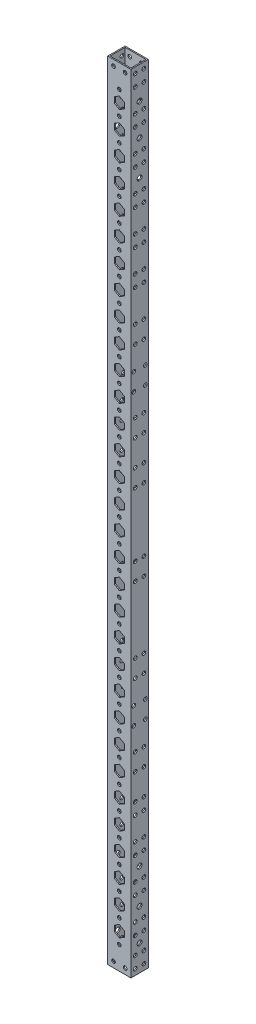
SolidWorks part; units mm, degrees
ref_plane "前视基准面" through (0, 0, 0) normal (0, 0, 1) x (1, 0, 0)
ref_plane "上视基准面" through (0, 0, 0) normal (0, 1, 0) x (1, 0, 0)
ref_plane "右视基准面" through (0, 0, 0) normal (1, 0, 0) x (0, 0, -1)
other "Configuration Table"
sketch "草图1" plane through (0, 0, 0) normal (0, 1, 0) x (1, 0, 0)
  line L1 (-10, -7.5) -> (10, -7.5)
  line L2 (-10, -7.5) -> (-10, 7.5)
  line L3 (-10, 7.5) -> (10, 7.5)
  line L4 (10, -7.5) -> (10, 7.5)
  line L5 (-10, -7.5) -> (10, 7.5) construction
  line L6 (-10, 7.5) -> (10, -7.5) construction
  point P0 (0, 0)
  dimension "D1" = 15
  dimension "D2" = 20
extrude "拉伸-薄壁1" add sketch "草图1" along normal blind 680 thin thin type one direction reverse wall 1
sketch "草图2" plane through (0, 0, -7.5) normal (0, 0, -1) x (-1, 0, 0)
  line L0 (0, 680) -> (0, 670) construction
  line L1 (-10, 680) -> (10, 680) construction
  line L2 (0, 670) -> (-10, 670) construction
  line L3 (-10, 680) -> (-10, 0) construction
  line L4 (10, 340) -> (-10, 340) construction
  line L5 (10, 680) -> (10, 0) construction
  line L6 (0, 10) -> (-10, 10) construction
  line L7 (0, 0) -> (0, 10) construction
  line L8 (0, 20) -> (0, 40) construction
  line L9 (-4.3301, 32.5008) -> (-4.3301, 27.5008)
  line L10 (-4.3301, 27.5008) -> (0, 25.0008)
  line L11 (0, 25.0008) -> (4.3301, 27.5008)
  line L12 (4.3301, 27.5008) -> (4.3301, 32.5008)
  line L13 (4.3301, 32.5008) -> (0, 35.0008)
  line L14 (0, 35.0008) -> (-4.3301, 32.5008)
  line L15 (0, 55.0008) -> (-4.3301, 52.5008)
  line L16 (4.3301, 52.5008) -> (0, 55.0008)
  line L17 (4.3301, 47.5008) -> (4.3301, 52.5008)
  line L18 (-4.3301, 52.5008) -> (-4.3301, 47.5008)
  line L19 (-4.3301, 47.5008) -> (0, 45.0008)
  line L20 (0, 45.0008) -> (4.3301, 47.5008)
  line L21 (0, 75.0008) -> (-4.3301, 72.5008)
  line L22 (4.3301, 72.5008) -> (0, 75.0008)
  line L23 (4.3301, 67.5008) -> (4.3301, 72.5008)
  line L24 (-4.3301, 72.5008) -> (-4.3301, 67.5008)
  line L25 (-4.3301, 67.5008) -> (0, 65.0008)
  line L26 (0, 65.0008) -> (4.3301, 67.5008)
  line L27 (0, 95.0008) -> (-4.3301, 92.5008)
  line L28 (4.3301, 92.5008) -> (0, 95.0008)
  line L29 (4.3301, 87.5008) -> (4.3301, 92.5008)
  line L30 (-4.3301, 92.5008) -> (-4.3301, 87.5008)
  line L31 (-4.3301, 87.5008) -> (0, 85.0008)
  line L32 (0, 85.0008) -> (4.3301, 87.5008)
  line L33 (0, 115.0008) -> (-4.3301, 112.5008)
  line L34 (4.3301, 112.5008) -> (0, 115.0008)
  line L35 (4.3301, 107.5008) -> (4.3301, 112.5008)
  line L36 (-4.3301, 112.5008) -> (-4.3301, 107.5008)
  line L37 (-4.3301, 107.5008) -> (0, 105.0008)
  line L38 (0, 105.0008) -> (4.3301, 107.5008)
  line L39 (0, 135.0008) -> (-4.3301, 132.5008)
  line L40 (4.3301, 132.5008) -> (0, 135.0008)
  line L41 (4.3301, 127.5008) -> (4.3301, 132.5008)
  line L42 (-4.3301, 132.5008) -> (-4.3301, 127.5008)
  line L43 (-4.3301, 127.5008) -> (0, 125.0008)
  line L44 (0, 125.0008) -> (4.3301, 127.5008)
  line L45 (0, 155.0008) -> (-4.3301, 152.5008)
  line L46 (4.3301, 152.5008) -> (0, 155.0008)
  line L47 (4.3301, 147.5008) -> (4.3301, 152.5008)
  line L48 (-4.3301, 152.5008) -> (-4.3301, 147.5008)
  line L49 (-4.3301, 147.5008) -> (0, 145.0008)
  line L50 (0, 145.0008) -> (4.3301, 147.5008)
  line L51 (0, 175.0008) -> (-4.3301, 172.5008)
  line L52 (4.3301, 172.5008) -> (0, 175.0008)
  line L53 (4.3301, 167.5008) -> (4.3301, 172.5008)
  line L54 (-4.3301, 172.5008) -> (-4.3301, 167.5008)
  line L55 (-4.3301, 167.5008) -> (0, 165.0008)
  line L56 (0, 165.0008) -> (4.3301, 167.5008)
  line L57 (0, 195.0008) -> (-4.3301, 192.5008)
  line L58 (4.3301, 192.5008) -> (0, 195.0008)
  line L59 (4.3301, 187.5008) -> (4.3301, 192.5008)
  line L60 (-4.3301, 192.5008) -> (-4.3301, 187.5008)
  line L61 (-4.3301, 187.5008) -> (0, 185.0008)
  line L62 (0, 185.0008) -> (4.3301, 187.5008)
  line L63 (0, 215.0008) -> (-4.3301, 212.5008)
  line L64 (4.3301, 212.5008) -> (0, 215.0008)
  line L65 (4.3301, 207.5008) -> (4.3301, 212.5008)
  line L66 (-4.3301, 212.5008) -> (-4.3301, 207.5008)
  line L67 (-4.3301, 207.5008) -> (0, 205.0008)
  line L68 (0, 205.0008) -> (4.3301, 207.5008)
  line L69 (0, 235.0008) -> (-4.3301, 232.5008)
  line L70 (4.3301, 232.5008) -> (0, 235.0008)
  line L71 (4.3301, 227.5008) -> (4.3301, 232.5008)
  line L72 (-4.3301, 232.5008) -> (-4.3301, 227.5008)
  line L73 (-4.3301, 227.5008) -> (0, 225.0008)
  line L74 (0, 225.0008) -> (4.3301, 227.5008)
  line L75 (0, 255.0008) -> (-4.3301, 252.5008)
  line L76 (4.3301, 252.5008) -> (0, 255.0008)
  line L77 (4.3301, 247.5008) -> (4.3301, 252.5008)
  line L78 (-4.3301, 252.5008) -> (-4.3301, 247.5008)
  line L79 (-4.3301, 247.5008) -> (0, 245.0008)
  line L80 (0, 245.0008) -> (4.3301, 247.5008)
  line L81 (0, 275.0008) -> (-4.3301, 272.5008)
  line L82 (4.3301, 272.5008) -> (0, 275.0008)
  line L83 (4.3301, 267.5008) -> (4.3301, 272.5008)
  line L84 (-4.3301, 272.5008) -> (-4.3301, 267.5008)
  line L85 (-4.3301, 267.5008) -> (0, 265.0008)
  line L86 (0, 265.0008) -> (4.3301, 267.5008)
  line L87 (0, 295.0008) -> (-4.3301, 292.5008)
  line L88 (4.3301, 292.5008) -> (0, 295.0008)
  line L89 (4.3301, 287.5008) -> (4.3301, 292.5008)
  line L90 (-4.3301, 292.5008) -> (-4.3301, 287.5008)
  line L91 (-4.3301, 287.5008) -> (0, 285.0008)
  line L92 (0, 285.0008) -> (4.3301, 287.5008)
  line L93 (0, 315.0008) -> (-4.3301, 312.5008)
  line L94 (4.3301, 312.5008) -> (0, 315.0008)
  line L95 (4.3301, 307.5008) -> (4.3301, 312.5008)
  line L96 (-4.3301, 312.5008) -> (-4.3301, 307.5008)
  line L97 (-4.3301, 307.5008) -> (0, 305.0008)
  line L98 (0, 305.0008) -> (4.3301, 307.5008)
  line L99 (0, 335.0008) -> (-4.3301, 332.5008)
  line L100 (4.3301, 332.5008) -> (0, 335.0008)
  line L101 (4.3301, 327.5008) -> (4.3301, 332.5008)
  line L102 (-4.3301, 332.5008) -> (-4.3301, 327.5008)
  line L103 (-4.3301, 327.5008) -> (0, 325.0008)
  line L104 (0, 325.0008) -> (4.3301, 327.5008)
  line L105 (0, 355.0008) -> (-4.3301, 352.5008)
  line L106 (4.3301, 352.5008) -> (0, 355.0008)
  line L107 (4.3301, 347.5008) -> (4.3301, 352.5008)
  line L108 (-4.3301, 352.5008) -> (-4.3301, 347.5008)
  line L109 (-4.3301, 347.5008) -> (0, 345.0008)
  line L110 (0, 345.0008) -> (4.3301, 347.5008)
  line L111 (0, 375.0008) -> (-4.3301, 372.5008)
  line L112 (4.3301, 372.5008) -> (0, 375.0008)
  line L113 (4.3301, 367.5008) -> (4.3301, 372.5008)
  line L114 (-4.3301, 372.5008) -> (-4.3301, 367.5008)
  line L115 (-4.3301, 367.5008) -> (0, 365.0008)
  line L116 (0, 365.0008) -> (4.3301, 367.5008)
  line L117 (0, 395.0008) -> (-4.3301, 392.5008)
  line L118 (4.3301, 392.5008) -> (0, 395.0008)
  line L119 (4.3301, 387.5008) -> (4.3301, 392.5008)
  line L120 (-4.3301, 392.5008) -> (-4.3301, 387.5008)
  line L121 (-4.3301, 387.5008) -> (0, 385.0008)
  line L122 (0, 385.0008) -> (4.3301, 387.5008)
  line L123 (0, 415.0008) -> (-4.3301, 412.5008)
  line L124 (4.3301, 412.5008) -> (0, 415.0008)
  line L125 (4.3301, 407.5008) -> (4.3301, 412.5008)
  line L126 (-4.3301, 412.5008) -> (-4.3301, 407.5008)
  line L127 (-4.3301, 407.5008) -> (0, 405.0008)
  line L128 (0, 405.0008) -> (4.3301, 407.5008)
  line L129 (0, 435.0008) -> (-4.3301, 432.5008)
  line L130 (4.3301, 432.5008) -> (0, 435.0008)
  line L131 (4.3301, 427.5008) -> (4.3301, 432.5008)
  line L132 (-4.3301, 432.5008) -> (-4.3301, 427.5008)
  line L133 (-4.3301, 427.5008) -> (0, 425.0008)
  line L134 (0, 425.0008) -> (4.3301, 427.5008)
  line L135 (0, 455.0008) -> (-4.3301, 452.5008)
  line L136 (4.3301, 452.5008) -> (0, 455.0008)
  line L137 (4.3301, 447.5008) -> (4.3301, 452.5008)
  line L138 (-4.3301, 452.5008) -> (-4.3301, 447.5008)
  line L139 (-4.3301, 447.5008) -> (0, 445.0008)
  line L140 (0, 445.0008) -> (4.3301, 447.5008)
  line L141 (0, 475.0008) -> (-4.3301, 472.5008)
  line L142 (4.3301, 472.5008) -> (0, 475.0008)
  line L143 (4.3301, 467.5008) -> (4.3301, 472.5008)
  line L144 (-4.3301, 472.5008) -> (-4.3301, 467.5008)
  line L145 (-4.3301, 467.5008) -> (0, 465.0008)
  line L146 (0, 465.0008) -> (4.3301, 467.5008)
  line L147 (0, 495.0008) -> (-4.3301, 492.5008)
  line L148 (4.3301, 492.5008) -> (0, 495.0008)
  line L149 (4.3301, 487.5008) -> (4.3301, 492.5008)
  line L150 (-4.3301, 492.5008) -> (-4.3301, 487.5008)
  line L151 (-4.3301, 487.5008) -> (0, 485.0008)
  line L152 (0, 485.0008) -> (4.3301, 487.5008)
  line L153 (0, 515.0008) -> (-4.3301, 512.5008)
  line L154 (4.3301, 512.5008) -> (0, 515.0008)
  line L155 (4.3301, 507.5008) -> (4.3301, 512.5008)
  line L156 (-4.3301, 512.5008) -> (-4.3301, 507.5008)
  line L157 (-4.3301, 507.5008) -> (0, 505.0008)
  line L158 (0, 505.0008) -> (4.3301, 507.5008)
  line L159 (0, 535.0008) -> (-4.3301, 532.5008)
  line L160 (4.3301, 532.5008) -> (0, 535.0008)
  line L161 (4.3301, 527.5008) -> (4.3301, 532.5008)
  line L162 (-4.3301, 532.5008) -> (-4.3301, 527.5008)
  line L163 (-4.3301, 527.5008) -> (0, 525.0008)
  line L164 (0, 525.0008) -> (4.3301, 527.5008)
  line L165 (0, 555.0008) -> (-4.3301, 552.5008)
  line L166 (4.3301, 552.5008) -> (0, 555.0008)
  line L167 (4.3301, 547.5008) -> (4.3301, 552.5008)
  line L168 (-4.3301, 552.5008) -> (-4.3301, 547.5008)
  line L169 (-4.3301, 547.5008) -> (0, 545.0008)
  line L170 (0, 545.0008) -> (4.3301, 547.5008)
  line L171 (0, 575.0008) -> (-4.3301, 572.5008)
  line L172 (4.3301, 572.5008) -> (0, 575.0008)
  line L173 (4.3301, 567.5008) -> (4.3301, 572.5008)
  line L174 (-4.3301, 572.5008) -> (-4.3301, 567.5008)
  line L175 (-4.3301, 567.5008) -> (0, 565.0008)
  line L176 (0, 565.0008) -> (4.3301, 567.5008)
  line L177 (0, 595.0008) -> (-4.3301, 592.5008)
  line L178 (4.3301, 592.5008) -> (0, 595.0008)
  line L179 (4.3301, 587.5008) -> (4.3301, 592.5008)
  line L180 (-4.3301, 592.5008) -> (-4.3301, 587.5008)
  line L181 (-4.3301, 587.5008) -> (0, 585.0008)
  line L182 (0, 585.0008) -> (4.3301, 587.5008)
  line L183 (0, 615.0008) -> (-4.3301, 612.5008)
  line L184 (4.3301, 612.5008) -> (0, 615.0008)
  line L185 (4.3301, 607.5008) -> (4.3301, 612.5008)
  line L186 (-4.3301, 612.5008) -> (-4.3301, 607.5008)
  line L187 (-4.3301, 607.5008) -> (0, 605.0008)
  line L188 (0, 605.0008) -> (4.3301, 607.5008)
  line L189 (0, 635.0008) -> (-4.3301, 632.5008)
  line L190 (4.3301, 632.5008) -> (0, 635.0008)
  line L191 (4.3301, 627.5008) -> (4.3301, 632.5008)
  line L192 (-4.3301, 632.5008) -> (-4.3301, 627.5008)
  line L193 (-4.3301, 627.5008) -> (0, 625.0008)
  line L194 (0, 625.0008) -> (4.3301, 627.5008)
  line L195 (0, 655.0008) -> (-4.3301, 652.5008)
  line L196 (4.3301, 652.5008) -> (0, 655.0008)
  line L197 (4.3301, 647.5008) -> (4.3301, 652.5008)
  line L198 (-4.3301, 652.5008) -> (-4.3301, 647.5008)
  line L199 (-4.3301, 647.5008) -> (0, 645.0008)
  line L200 (0, 645.0008) -> (4.3301, 647.5008)
  circle A0 centre (-5, 675) radius 1.575
  circle A1 centre (5, 675) radius 1.575
  circle A2 centre (5, 5) radius 1.575
  circle A3 centre (-5, 5) radius 1.575
  circle A4 centre (0, 660) radius 1.575
  circle A5 centre (0, 640) radius 1.575
  circle A6 centre (0, 620) radius 1.575
  circle A7 centre (0, 600) radius 1.575
  circle A8 centre (0, 580) radius 1.575
  circle A9 centre (0, 560) radius 1.575
  circle A10 centre (0, 540) radius 1.575
  circle A11 centre (0, 520) radius 1.575
  circle A12 centre (0, 500) radius 1.575
  circle A13 centre (0, 480) radius 1.575
  circle A14 centre (0, 460) radius 1.575
  circle A15 centre (0, 440) radius 1.575
  circle A16 centre (0, 420) radius 1.575
  circle A17 centre (0, 400) radius 1.575
  circle A18 centre (0, 380) radius 1.575
  circle A19 centre (0, 360) radius 1.575
  circle A20 centre (0, 340) radius 1.575
  circle A21 centre (0, 320) radius 1.575
  circle A22 centre (0, 300) radius 1.575
  circle A23 centre (0, 280) radius 1.575
  circle A24 centre (0, 260) radius 1.575
  circle A25 centre (0, 240) radius 1.575
  circle A26 centre (0, 220) radius 1.575
  circle A27 centre (0, 200) radius 1.575
  circle A28 centre (0, 180) radius 1.575
  circle A29 centre (0, 160) radius 1.575
  circle A30 centre (0, 140) radius 1.575
  circle A31 centre (0, 120) radius 1.575
  circle A32 centre (0, 100) radius 1.575
  circle A33 centre (0, 80) radius 1.575
  circle A34 centre (0, 60) radius 1.575
  circle A35 centre (0, 40) radius 1.575
  circle A36 centre (0, 20) radius 1.575
  circle A37 centre (0, 30.0008) radius 4.3301 construction
  dimension "D2" = 3.15
  dimension "D5" = 3.15
  dimension "D1" = 10
  dimension "D3" = 5
  dimension "D4" = 5
  dimension "D6" = 10
  dimension "D8" = 20
  dimension "D9" = 5
  dimension "D10" = 9.9992
  dimension "D11" = 20
  dimension "D7" = 33
extrude "切除-拉伸1" cut sketch "草图2" against normal through all
sketch "草图3" plane through (-10, 0, 0) normal (-1, 0, 0) x (0, 0, 1)
  line L0 (-7.5, 445) -> (7.5, 445) construction
  line L1 (-7.5, 680) -> (-7.5, 0) construction
  line L2 (7.5, 680) -> (7.5, 0) construction
  line L3 (-7.5, 680) -> (7.5, 680) construction
  line L4 (0, 445) -> (0, 680) construction
  line L5 (-7.5, 195) -> (7.5, 195) construction
  line L6 (-7.5, 160) -> (7.5, 160) construction
  line L7 (-7.5, 480) -> (7.5, 480) construction
  line L8 (-7.5, 230) -> (7.5, 230) construction
  line L9 (-7.5, 10) -> (7.5, 10) construction
  line L10 (0, 10) -> (0, 0) construction
  line L11 (-7.5, 0) -> (7.5, 0) construction
  line L12 (0, 337.5) -> (7.5, 337.5) construction
  line L13 (0, 445) -> (0, 230) construction
  line L14 (-7.5, 372.5) -> (7.5, 372.5) construction
  line L15 (-7.5, 302.5) -> (7.5, 302.5) construction
  line L16 (-7.5, 670) -> (7.5, 670) construction
  line L17 (0, 10) -> (0, 22.5) construction
  line L18 (0, 22.5) -> (0, 50) construction
  line L19 (0, 50) -> (0, 80) construction
  circle A0 centre (-5, 452.5) radius 1.575
  circle A1 centre (5, 452.5) radius 1.575
  circle A2 centre (5, 437.5) radius 1.575
  circle A3 centre (-5, 437.5) radius 1.575
  circle A4 centre (-5, 202.5) radius 1.575
  circle A5 centre (5, 202.5) radius 1.575
  circle A6 centre (5, 187.5) radius 1.575
  circle A7 centre (-5, 187.5) radius 1.575
  circle A8 centre (-3.75, 487.5) radius 1.575
  circle A9 centre (-3.75, 472.5) radius 1.575
  circle A10 centre (3.75, 472.5) radius 1.575
  circle A11 centre (3.75, 487.5) radius 1.575
  circle A12 centre (3.75, 417.5) radius 1.575
  circle A13 centre (-3.75, 417.5) radius 1.575
  circle A14 centre (3.75, 402.5) radius 1.575
  circle A15 centre (-3.75, 402.5) radius 1.575
  circle A16 centre (-3.75, 167.5) radius 1.575
  circle A17 centre (3.75, 167.5) radius 1.575
  circle A18 centre (3.75, 152.5) radius 1.575
  circle A19 centre (-3.75, 152.5) radius 1.575
  circle A20 centre (-3.75, 237.5) radius 1.575
  circle A21 centre (3.75, 237.5) radius 1.575
  circle A22 centre (3.75, 222.5) radius 1.575
  circle A23 centre (-3.75, 222.5) radius 1.575
  circle A24 centre (3.75, 5) radius 1.6
  circle A25 centre (-3.75, 5) radius 1.6
  circle A26 centre (3.75, 15) radius 1.6
  circle A27 centre (-3.75, 15) radius 1.6
  circle A28 centre (3.75, 365) radius 1.6
  circle A29 centre (-3.75, 365) radius 1.6
  circle A30 centre (-3.75, 380) radius 1.6
  circle A31 centre (3.75, 380) radius 1.6
  circle A32 centre (3.75, 295) radius 1.6
  circle A33 centre (-3.75, 295) radius 1.6
  circle A34 centre (-3.75, 310) radius 1.6
  circle A35 centre (3.75, 310) radius 1.6
  circle A36 centre (-3.75, 675) radius 1.6
  circle A37 centre (3.75, 675) radius 1.6
  circle A38 centre (3.75, 665) radius 1.6
  circle A39 centre (-3.75, 665) radius 1.6
  circle A40 centre (-3.75, 645) radius 1.6
  circle A41 centre (3.75, 645) radius 1.6
  circle A42 centre (-3.75, 635) radius 1.6
  circle A43 centre (3.75, 635) radius 1.6
  circle A44 centre (-3.75, 615) radius 1.6
  circle A45 centre (3.75, 615) radius 1.6
  circle A46 centre (-3.75, 605) radius 1.6
  circle A47 centre (3.75, 605) radius 1.6
  circle A48 centre (-3.75, 585) radius 1.6
  circle A49 centre (3.75, 585) radius 1.6
  circle A50 centre (-3.75, 575) radius 1.6
  circle A51 centre (3.75, 575) radius 1.6
  circle A52 centre (-3.75, 555) radius 1.6
  circle A53 centre (3.75, 555) radius 1.6
  circle A54 centre (-3.75, 545) radius 1.6
  circle A55 centre (3.75, 545) radius 1.6
  circle A56 centre (-3.75, 525) radius 1.6
  circle A57 centre (3.75, 525) radius 1.6
  circle A58 centre (-3.75, 515) radius 1.6
  circle A59 centre (3.75, 515) radius 1.6
  circle A60 centre (3.75, 130) radius 1.6
  circle A61 centre (-3.75, 130) radius 1.6
  circle A62 centre (3.75, 120) radius 1.6
  circle A63 centre (-3.75, 120) radius 1.6
  circle A64 centre (3.75, 100) radius 1.6
  circle A65 centre (-3.75, 100) radius 1.6
  circle A66 centre (3.75, 90) radius 1.6
  circle A67 centre (-3.75, 90) radius 1.6
  circle A68 centre (3.75, 70) radius 1.6
  circle A69 centre (-3.75, 70) radius 1.6
  circle A70 centre (3.75, 60) radius 1.6
  circle A71 centre (-3.75, 60) radius 1.6
  circle A72 centre (3.75, 40) radius 1.6
  circle A73 centre (-3.75, 40) radius 1.6
  circle A74 centre (3.75, 30) radius 1.6
  circle A75 centre (-3.75, 30) radius 1.6
  circle A76 centre (0, 22.5) radius 2.1
  circle A77 centre (0, 50) radius 2.1
  circle A78 centre (0, 652.5) radius 2.1
  circle A79 centre (0, 625) radius 2.1
  circle A80 centre (0, 80) radius 2.1
  circle A81 centre (0, 595) radius 2.1
  dimension "D3" = 3.15
  dimension "D6" = 3.15
  dimension "D11" = 3.15
  dimension "D14" = 3.15
  dimension "D17" = 3.2
  dimension "D22" = 3.2
  dimension "D25" = 3.2
  dimension "D30" = 4.2
  dimension "D32" = 4.2
  dimension "D35" = 4.2
  dimension "D1" = 235
  dimension "D2" = 5
  dimension "D4" = 7.5
  dimension "D5" = 250
  dimension "D7" = 7.5
  dimension "D8" = 5
  dimension "D9" = 35
  dimension "D10" = 35
  dimension "D12" = 3.75
  dimension "D13" = 7.5
  dimension "D15" = 7.5
  dimension "D16" = 3.75
  dimension "D18" = 5
  dimension "D19" = 10
  dimension "D20" = 3.75
  dimension "D21" = 35
  dimension "D23" = 3.75
  dimension "D24" = 7.5
  dimension "D26" = 3.75
  dimension "D27" = 5
  dimension "D28" = 10
  dimension "D29" = 30
  dimension "D31" = 12.5
  dimension "D33" = 40
  dimension "D34" = 30
extrude "切除-拉伸2" cut sketch "草图3" against normal through all
